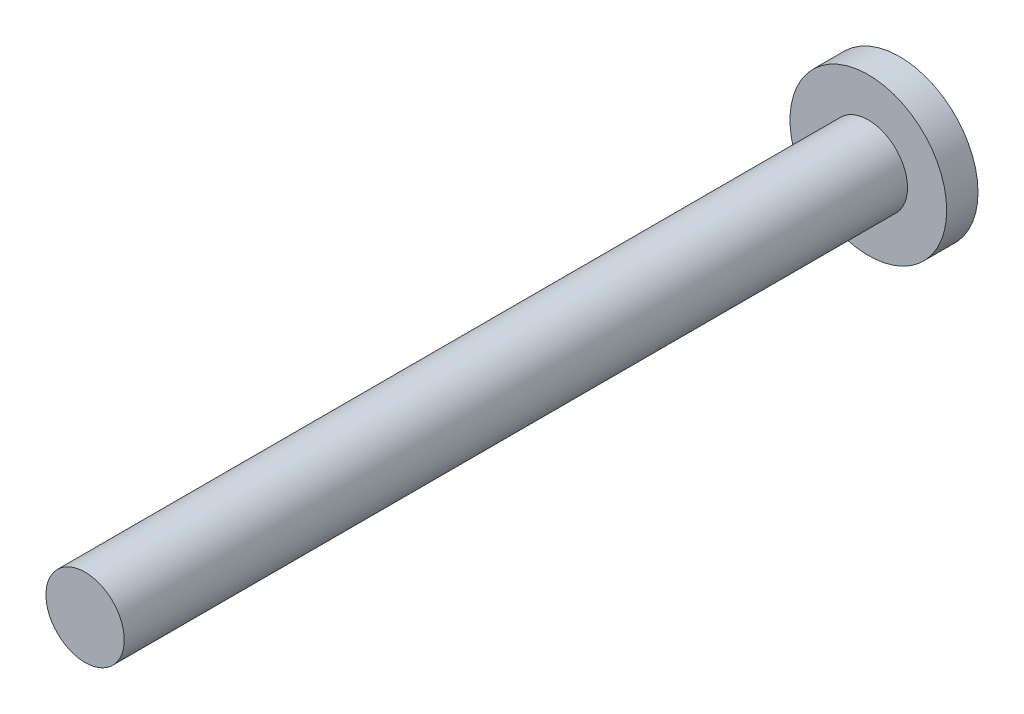
SolidWorks part; units mm, degrees
ref_plane "Front Plane" through (0, 0, 0) normal (0, 0, 1) x (1, 0, 0)
ref_plane "Top Plane" through (0, 0, 0) normal (0, 1, 0) x (1, 0, 0)
ref_plane "Right Plane" through (0, 0, 0) normal (1, 0, 0) x (0, 0, -1)
sketch "Sketch1" plane through (0, 0, 0) normal (0, 1, 0) x (1, 0, 0)
  line L0 (0, 0) -> (0, 52)
  line L1 (0, 52) -> (5, 52)
  line L2 (5, 52) -> (5, 50)
  line L3 (5, 50) -> (2.5, 50)
  line L4 (2.5, 50) -> (2.5, 0)
  line L5 (2.5, 0) -> (0, 0)
  dimension "D1" = 50
  dimension "D2" = 2
  dimension "D3" = 2.5
  dimension "D4" = 5
revolve "Revolve2" add sketch "Sketch1" angle 360 about L0
